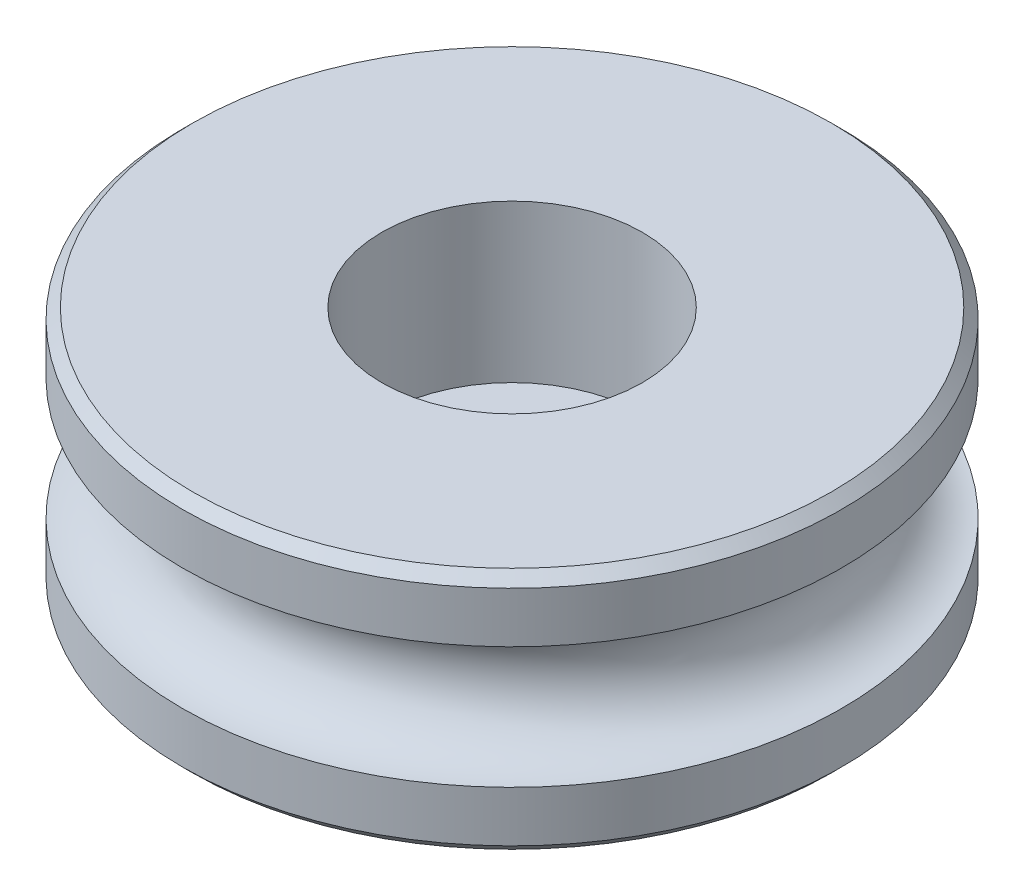
SolidWorks part; units mm, degrees
material "PVC 0.007 Plasticized"
ref_plane "Front Plane" through (0, 0, 0) normal (0, 0, 1) x (1, 0, 0)
ref_plane "Top Plane" through (0, 0, 0) normal (0, 1, 0) x (1, 0, 0)
ref_plane "Right Plane" through (0, 0, 0) normal (1, 0, 0) x (0, 0, -1)
sketch "Sketch1" plane through (0, 0, 0) normal (0, 0, 1) x (1, 0, 0)
  line L0 (7, 0) -> (31.5, 0)
  line L1 (32.5, 1) -> (32.5, 6)
  line L2 (32.5, 18) -> (32.5, 23)
  line L3 (31.5, 24) -> (12.85, 24)
  line L4 (0, 24) -> (0, 0) construction
  line L5 (32.5, 23) -> (31.5, 24)
  line L6 (31.5, 0) -> (32.5, 1)
  line L7 (7, 0) -> (7, 8.5)
  line L9 (12.85, 24) -> (12.85, 8.5)
  line L10 (12.85, 8.5) -> (7, 8.5)
  arc A0 (32.5, 18) -> (32.5, 6) centre (32.5, 12) ccw
  point P1 (32.5, 0)
  point P5 (32.5, 24)
  dimension "D1" = 32.5
  dimension "D2" = 6
  dimension "D3" = 6
  dimension "D4" = 12
  dimension "D5" = 7
  dimension "D6" = 8.5
  dimension "D9" = 12.85
revolve "Revolve1" add sketch "Sketch1" angle 360 about L4
